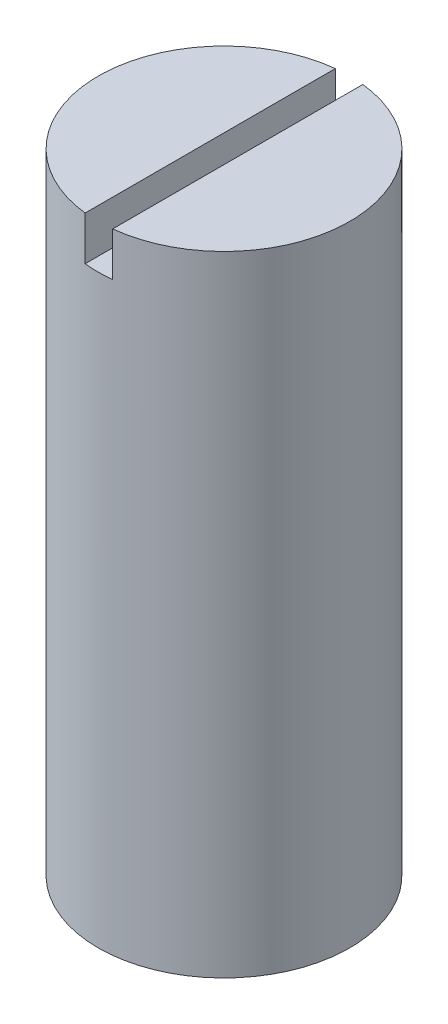
SolidWorks part; units mm, degrees
material "Gray Cast Iron"
ref_plane "Front Plane" through (0, 0, 0) normal (0, 0, 1) x (1, 0, 0)
ref_plane "Top Plane" through (0, 0, 0) normal (0, 1, 0) x (1, 0, 0)
ref_plane "Right Plane" through (0, 0, 0) normal (1, 0, 0) x (0, 0, -1)
sketch "Sketch1" plane through (0, 0, 0) normal (0, 1, 0) x (1, 0, 0)
  circle A0 centre (0, 0) radius 16
  dimension "D1" = 32
extrude "Boss-Extrude1" add sketch "Sketch1" along normal blind 80
sketch "Sketch2" plane through (0, 0, 0) normal (0, 0, 1) x (1, 0, 0)
  line L0 (-1.75, 74.4125) -> (1.75, 74.4125)
  line L1 (1.75, 74.4125) -> (1.75, 82)
  line L2 (1.75, 82) -> (-1.75, 82)
  line L3 (-1.75, 82) -> (-1.75, 74.4125)
  dimension "D1" = 3.5
  dimension "D2" = 7.5875
  dimension "D3" = 1.75
  dimension "D4" = 74.4125
extrude "Cut-Extrude1" cut sketch "Sketch2" against normal mid plane 36
